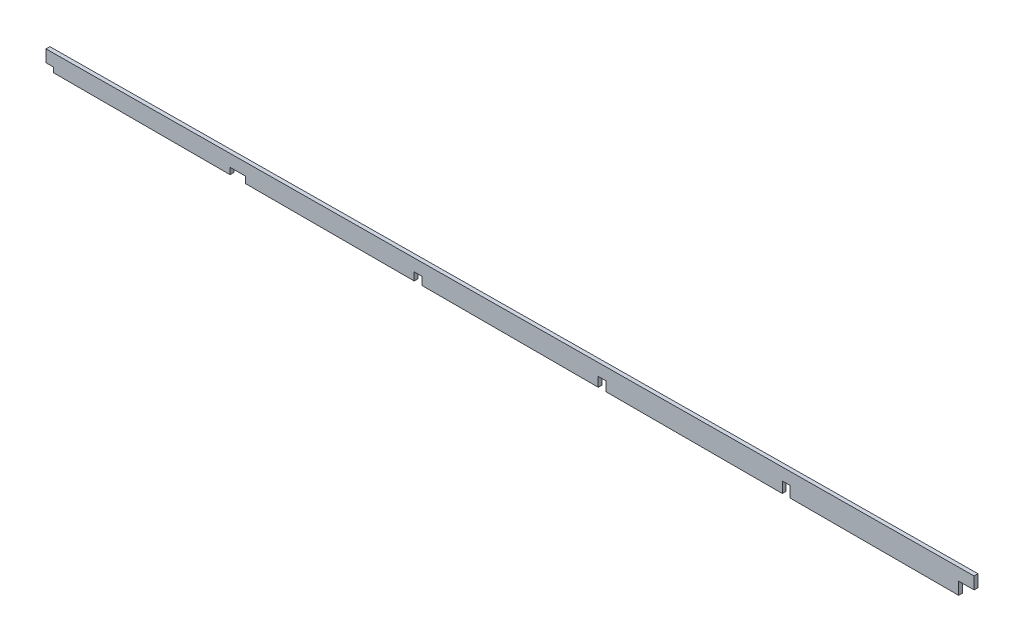
SolidWorks part; units mm, degrees
material "Balsa"
ref_plane "Front Plane" through (0, 0, 0) normal (0, 0, 1) x (1, 0, 0)
ref_plane "Top Plane" through (0, 0, 0) normal (0, 1, 0) x (1, 0, 0)
ref_plane "Right Plane" through (0, 0, 0) normal (1, 0, 0) x (0, 0, -1)
sketch "Sketch1" plane through (0, 0, 0) normal (0, 0, 1) x (1, 0, 0)
  line L0 (88.3256, -0.5662) -> (88.3256, 4.4066)
  line L1 (88.3256, 4.4066) -> (-292.6744, 1.2912)
  line L2 (-292.6744, 1.2912) -> (-292.6744, -3.6641)
  line L3 (-217.1094, -3.0497) -> (-210.7594, -2.9981)
  line L5 (-289.4994, -5.6703) -> (-217.1094, -5.6703)
  line L6 (81.9756, -0.6178) -> (81.9756, -5.6703)
  line L7 (12.7606, -1.1806) -> (12.7606, -5.6703)
  line L8 (9.5856, -1.2064) -> (9.5856, -5.6703)
  line L9 (-65.9794, -1.8209) -> (-65.9794, -5.6703)
  line L10 (-62.8044, -1.7951) -> (-62.8044, -5.6703)
  line L11 (-141.5444, -2.4353) -> (-141.5444, -5.6703)
  line L12 (-138.3694, -2.4095) -> (-138.3694, -5.6703)
  line L13 (-217.1094, -3.0497) -> (-217.1094, -5.6703)
  line L14 (-210.7594, -2.9981) -> (-210.7594, -5.6703)
  line L15 (-210.7594, -5.6703) -> (-141.5444, -5.6703)
  line L16 (-141.5444, -2.4353) -> (-138.3694, -2.4095)
  line L17 (-138.3694, -5.6703) -> (-65.9794, -5.6703)
  line L18 (-65.9794, -1.8209) -> (-62.8044, -1.7951)
  line L19 (-62.8044, -5.6703) -> (9.5856, -5.6703)
  line L20 (9.5856, -1.2064) -> (12.7606, -1.1806)
  line L21 (12.7606, -5.6703) -> (81.9756, -5.6703)
  line L22 (81.9756, -0.6178) -> (88.3256, -0.5662)
  line L23 (-289.4994, -3.6383) -> (-289.4994, -5.6703)
  line L24 (-289.4994, -3.6383) -> (-292.6744, -3.6641)
  dimension "D1" = 2.032
extrude "Boss-Extrude2" add sketch "Sketch1" along normal up to surface (1.5875 mm away) contours L1 L2 L24 L23 L5 L13 L3 L14 L15 L11 L16 L12 L17 L9 L18 L10 L19 L8 L20 L7 L21 L6 L22 L0
